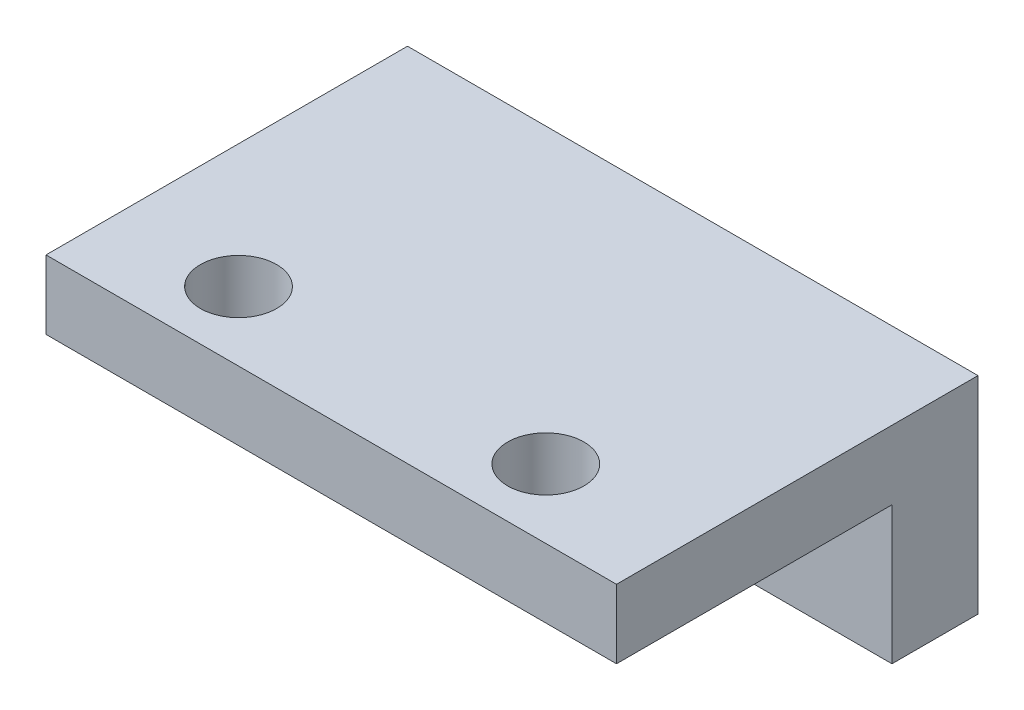
SolidWorks part; units mm, degrees
ref_plane "Front Plane" through (0, 0, 0) normal (0, 0, 1) x (1, 0, 0)
ref_plane "Top Plane" through (0, 0, 0) normal (0, 1, 0) x (1, 0, 0)
ref_plane "Right Plane" through (0, 0, 0) normal (1, 0, 0) x (0, 0, -1)
sketch "Sketch1" plane through (0, 0, 0) normal (0, 0, 1) x (1, 0, 0)
  line L0 (-40.8686, -32.1165) -> (-47.7102, -32.1165) construction
  line L2 (-16.1475, -28.3065) -> (-16.1475, -35.9265)
  line L3 (-16.1475, -35.9265) -> (-47.7102, -35.9265)
  line L4 (-47.7102, -28.3065) -> (-47.7102, -35.9265)
  line L7 (-47.7102, -28.3065) -> (-47.7102, -24.4965)
  line L8 (-47.7102, -24.4965) -> (-16.1475, -24.4965)
  line L9 (-16.1475, -28.3065) -> (-16.1475, -24.4965)
  circle A0 centre (-40.8686, -32.1165) radius 2
  circle A1 centre (-23.8686, -32.1165) radius 2
  dimension "D1" = 3.81
  dimension "D3" = 3.81
extrude "Boss-Extrude1" add sketch "Sketch1" along normal blind 20
sketch "Sketch2" plane through (0, 0, 20) normal (0, 0, 1) x (1, 0, 0)
  line L0 (-16.1475, -35.9265) -> (-16.1475, -24.4965) construction
  line L1 (-47.7102, -35.9265) -> (-16.1475, -35.9265)
  line L2 (-47.7102, -35.9265) -> (-47.7102, -28.3065)
  line L3 (-47.7102, -28.3065) -> (-16.1475, -28.3065)
  line L4 (-16.1475, -35.9265) -> (-16.1475, -28.3065)
  dimension "D1" = 7.62
extrude "Cut-Extrude1" cut sketch "Sketch2" against normal blind 15.24
sketch "Sketch4" plane through (0, 0, 0) normal (0, 0, -1) x (-1, 0, 0)
  line L0 (40.8686, -30.1165) -> (40.8686, -24.4965) construction
  line L1 (16.1475, -24.4965) -> (47.7102, -24.4965) construction
  line L2 (23.8686, -30.1165) -> (23.8686, -24.4965) construction
  circle A0 centre (40.8686, -32.1165) radius 2 construction
  circle A1 centre (23.8686, -32.1165) radius 2 construction
sketch "Sketch5" plane through (0, -24.4965, 0) normal (0, 1, 0) x (1, 0, 0)
  line L0 (-40.8686, 0) -> (-40.8686, -20) construction
  line L1 (-16.1475, -20) -> (-47.7102, -20) construction
  line L2 (-23.8686, 0) -> (-23.8686, -20) construction
  circle A0 centre (-23.8686, -16.19) radius 2.11
  circle A1 centre (-40.8686, -16.19) radius 2.11
  point P12 (0, 0)
  dimension "D1" = 4.22
  dimension "D2" = 4.22
  dimension "D3" = 3.81
  dimension "D4" = 3.81
extrude "Cut-Extrude2" cut sketch "Sketch5" against normal blind 10.414
